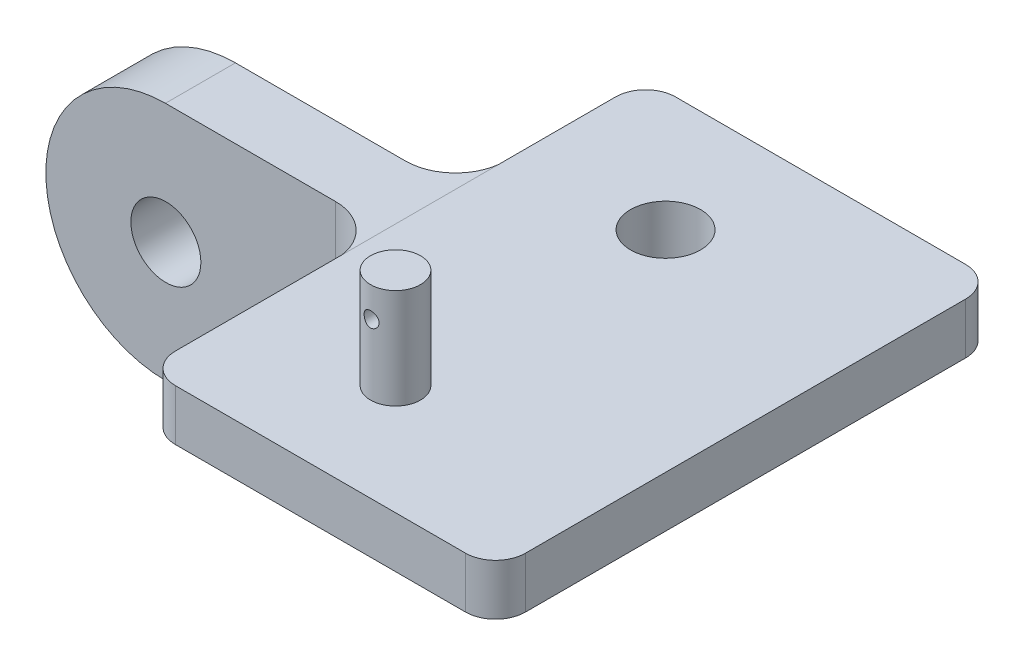
SolidWorks part; units mm, degrees
ref_plane "Front Plane" through (0, 0, 0) normal (0, 0, 1) x (1, 0, 0)
ref_plane "Top Plane" through (0, 0, 0) normal (0, 1, 0) x (1, 0, 0)
ref_plane "Right Plane" through (0, 0, 0) normal (1, 0, 0) x (0, 0, -1)
sketch "Sketch1" plane through (0, 0, 0) normal (0, 0, 1) x (1, 0, 0)
  line L5 (-10.4464, 5.9056) -> (10.4461, -5.9055) construction
  line L6 (-0.0433, 12) -> (21.9567, 12)
  line L9 (21.9567, 12) -> (21.9567, 7)
  arc A0 (-0.0433, 12) -> (0, -11.9999) centre (-0.0001, 0.0001) ccw
  circle A1 centre (-0.0001, 0.0001) radius 3.5
  arc A2 (0, -11.9999) -> (21.9567, 7) centre (-3.1355, 13.8103) ccw
  point P0 (0, 0)
  dimension "D1" = 12
  dimension "D3" = 7
  dimension "D5" = 26
  dimension "D2" = 22
  dimension "D4" = 5
extrude "Boss-Extrude1" add sketch "Sketch1" along normal blind 7
sketch "Sketch3" plane through (21.9567, 0, 0) normal (1, 0, 0) x (0, 0, -1)
  line L0 (-7, 7) -> (0, 12) construction
  line L2 (-26, 12.0511) -> (19, 12.0511)
  line L3 (-26, 12.0511) -> (-26, 6.9489)
  line L4 (-26, 6.9489) -> (19, 6.9489)
  line L5 (19, 12.0511) -> (19, 6.9489)
  line L6 (-26, 12.0511) -> (19, 6.9489) construction
  line L7 (-26, 6.9489) -> (19, 12.0511) construction
  point P4 (-3.5, 9.5)
  dimension "D1" = 45
extrude "Boss-Extrude3" add sketch "Sketch3" along normal blind 35
fillet "Fillet2" radius 5 1 edges at (21.9567, 9.5, 0)
fillet "Fillet6" radius 5 1 edges at (21.9567, 9.5, 7)
sketch "Sketch4" plane through (0, 12.0511, 0) normal (0, 1, 0) x (1, 0, 0)
  line L0 (56.9567, 19) -> (21.9567, -26) construction
  line L1 (21.9567, 19) -> (56.9567, -26) construction
  line L2 (56.9567, 19) -> (56.9567, -26) construction
  line L3 (21.9567, -3.5) -> (56.9567, -3.5) construction
  line L4 (21.9567, -12) -> (21.9567, 5) construction
  line L5 (56.9567, 19) -> (21.9567, 19) construction
  line L6 (21.9567, 19) -> (21.9567, -26) construction
  circle A0 centre (35.9567, 7) radius 3.5
  dimension "D1" = 7
  dimension "D2" = 12
  dimension "D3" = 14
extrude "Cut-Extrude1" cut sketch "Sketch4" against normal up to surface (5.1022 mm away) up to face at (39.4567, 6.9489, 3.5)
sketch "Sketch5" plane through (0, 12.0511, 0) normal (0, 1, 0) x (1, 0, 0)
  line L0 (21.9567, 19) -> (21.9567, -26) construction
  line L1 (56.9567, 19) -> (21.9567, 19) construction
  circle A0 centre (35.9567, -20) radius 2.5
  dimension "D1" = 5
  dimension "D2" = 14
  dimension "D3" = 39
extrude "Boss-Extrude4" add sketch "Sketch5" along normal blind 10
sketch "Sketch6" plane through (0, 0, 26) normal (0, 0, 1) x (1, 0, 0)
  line L1 (21.9567, 12.0511) -> (56.9567, 12.0511)
  line L2 (21.9567, 12.0511) -> (21.9567, 6.9489)
  line L3 (21.9567, 6.9489) -> (56.9567, 6.9489)
  line L4 (56.9567, 12.0511) -> (56.9567, 6.9489)
extrude "Boss-Extrude5" add sketch "Sketch6" along normal blind 5
fillet "Fillet14" radius 3 1 edges at (56.9567, 9.5, -19)
fillet "Fillet15" radius 3 3 edges at (21.9567, 9.5, -19) (21.9567, 9.5, 31) (56.9567, 9.5, 31)
sketch "Sketch7" plane through (0, 0, 31) normal (0, 0, 1) x (1, 0, 0)
  line L0 (33.4567, 22.0511) -> (33.4567, 12.0511) construction
  line L2 (38.4567, 22.0511) -> (33.4567, 22.0511) construction
  circle A0 centre (35.9567, 19.0511) radius 0.75
  dimension "D2" = 1.5
  dimension "D1" = 2.5
  dimension "D3" = 3
extrude "Cut-Extrude2" cut sketch "Sketch7" against normal blind 20
